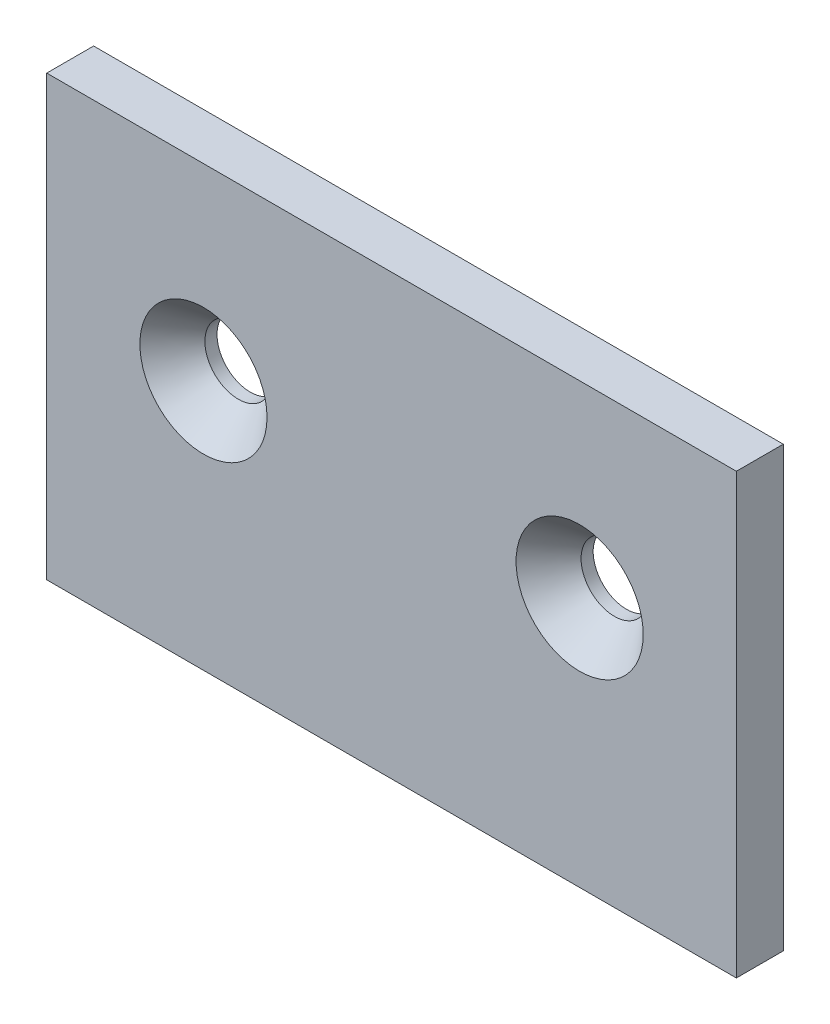
SolidWorks part; units mm, degrees
ref_plane "Front Plane" through (0, 0, 0) normal (0, 0, 1) x (1, 0, 0)
ref_plane "Top Plane" through (0, 0, 0) normal (0, 1, 0) x (1, 0, 0)
ref_plane "Right Plane" through (0, 0, 0) normal (1, 0, 0) x (0, 0, -1)
sketch "Sketch1" plane through (0, 0, 0) normal (0, 0, 1) x (1, 0, 0)
  line L1 (34.925, 0) -> (-34.925, 0)
  line L2 (34.925, 0) -> (34.925, 44.45)
  line L3 (34.925, 44.45) -> (-34.925, 44.45)
  line L4 (-34.925, 0) -> (-34.925, 44.45)
  dimension "D1" = 69.85
  dimension "D2" = 44.45
extrude "Boss-Extrude1" add sketch "Sketch1" along normal blind 4.7498
hole_wizard "CSK for 1/4 Flat Head Machine Screw1" positions "Sketch2" profile "Sketch3" countersink size "1/4" standard "ANSI Inch" end condition through all
sketch "Sketch2" plane through (0, 0, 4.7498) normal (0, 0, 1) x (1, 0, 0)
  line L0 (0, 0) -> (0, 25.4) construction
  point P6 (-19.05, 25.4)
  point P8 (19.05, 25.4)
  dimension "D1" = 38.1
sketch "Sketch3" plane through (19.05, 25.4, 4.7498) normal (1, 0, 0) x (0, -1, 0)
  line L0 (0, 0) -> (0, 4.7498)
  line L1 (0, 4.7498) -> (3.3782, 4.7498)
  line L2 (3.3782, 4.7498) -> (3.3782, 3.5209)
  line L3 (3.3782, 3.5209) -> (6.4389, 0)
  line L5 (6.4389, 0) -> (0, 0)
  line L6 (-3.3782, 3.5209) -> (-6.4389, 0) construction
  line L11 (0, -6.35) -> (0, 107.95) construction
  dimension "Thru Hole Dia." = 6.7564
  dimension "Thru Hole Depth" = 4.7498
  dimension "Near C'Sink Dia." = 12.8778
  dimension "Near C'Sink Angle" = 82
